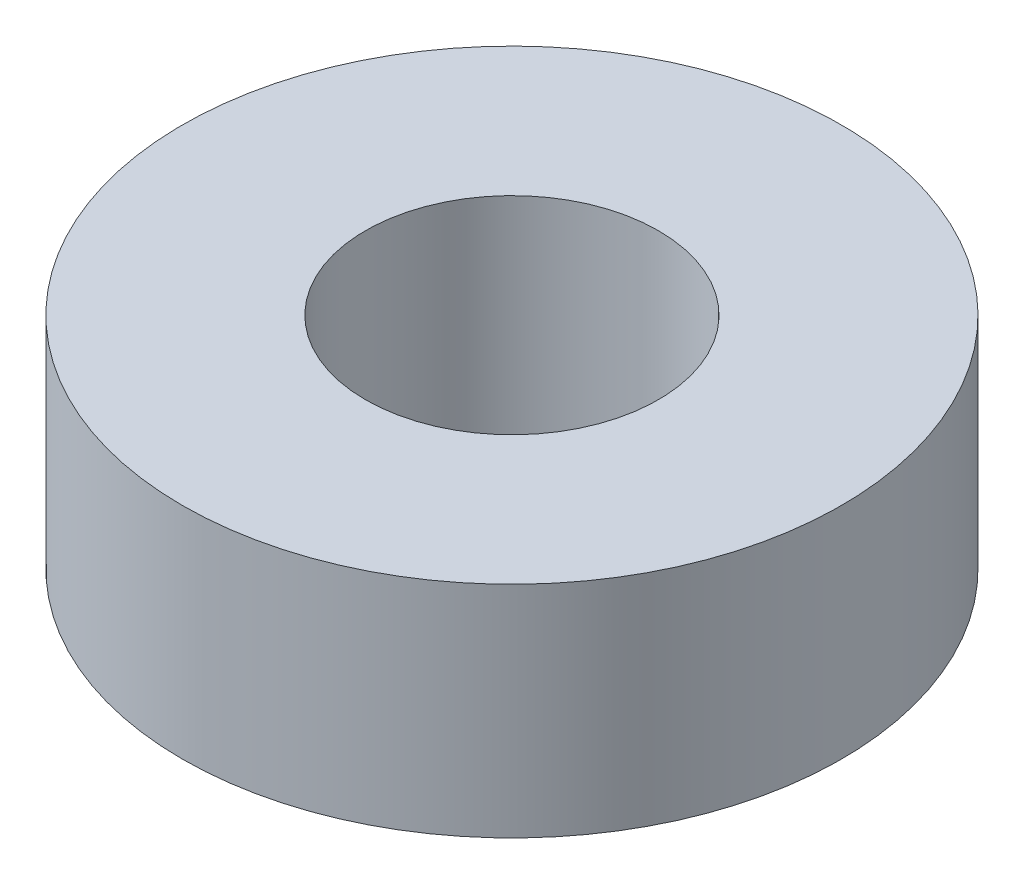
SolidWorks part; units mm, degrees
ref_plane "Ebene vorne" through (0, 0, 0) normal (0, 0, 1) x (1, 0, 0)
ref_plane "Ebene oben" through (0, 0, 0) normal (0, 1, 0) x (1, 0, 0)
ref_plane "Ebene rechts" through (0, 0, 0) normal (1, 0, 0) x (0, 0, -1)
sketch "Skizze1" plane through (0, 0, 0) normal (0, 1, 0) x (1, 0, 0)
  circle A0 centre (0, 0) radius 1.6
  circle A1 centre (0, 0) radius 3.6
  dimension "D1" = 3.2
  dimension "D2" = 2
extrude "Aufsatz-Linear austragen1" add sketch "Skizze1" along normal blind 2.4
